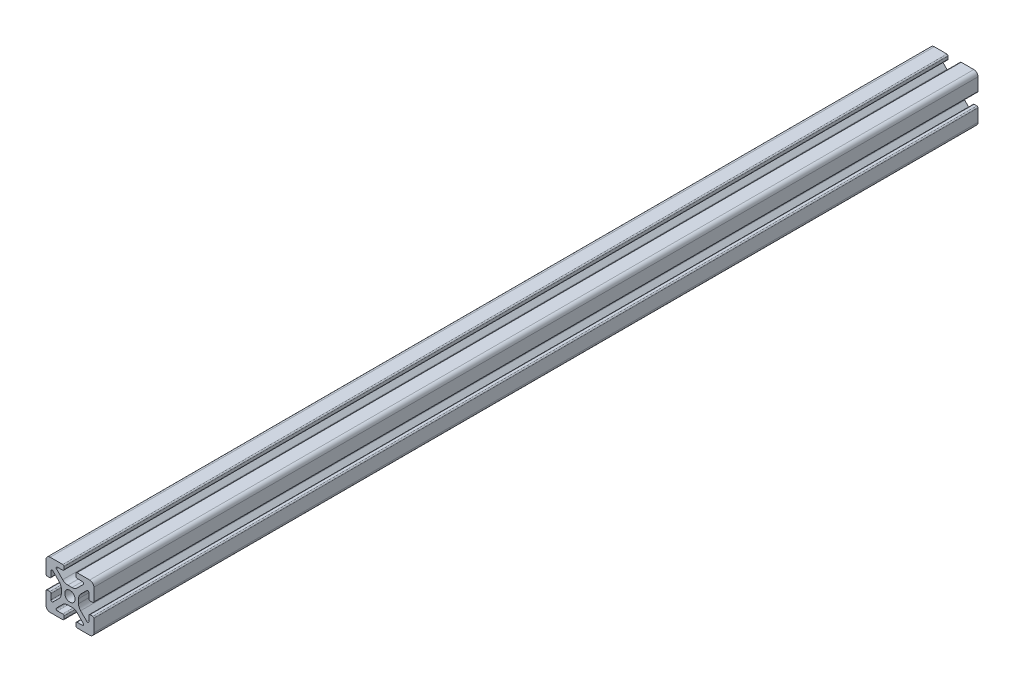
SolidWorks part; units mm, degrees
ref_plane "Front Plane" through (0, 0, 0) normal (0, 0, 1) x (1, 0, 0)
ref_plane "Top Plane" through (0, 0, 0) normal (0, 1, 0) x (1, 0, 0)
ref_plane "Right Plane" through (0, 0, 0) normal (1, 0, 0) x (0, 0, -1)
sketch "Sketch2" plane through (0, 0, 0) normal (0, 0, 1) x (1, 0, 0)
  line L0 (0, 10) -> (0, -10) construction
  line L1 (-10, 0) -> (10, 0) construction
  line L2 (2.5, -10) -> (10, -10)
  line L3 (10, -10) -> (10, -2.5)
  line L4 (2.5, -10) -> (2.5, -7.9246)
  line L5 (2.5, -7.9246) -> (6.4571, -7.9246)
  line L6 (6.4571, -7.9246) -> (2.1325, -3.6)
  line L7 (0, 0) -> (10, -10) construction
  line L8 (10, -2.5) -> (7.9246, -2.5)
  line L9 (7.9246, -2.5) -> (7.9246, -6.4571)
  line L10 (7.9246, -6.4571) -> (3.6, -2.1325)
  line L11 (5.7623, -4.2948) -> (4.2948, -5.7623) construction
  circle A0 centre (0, 0) radius 2.15
  arc A1 (5.25, -7.9246) -> (5.6036, -7.0711) centre (5.25, -7.4246) ccw construction
  point P8 (0, -3.6)
  point P16 (5.0286, -5.0286)
  dimension "Center Hole Diameter" = 4.3
  dimension "D3" = 0.5
  dimension "Rail Height" = 20
  dimension "Rail Width" = 20
  dimension "T-Slot Width" = 5
  dimension "Slot Depth" = 6.4
  dimension "Slot Inner Width" = 11.5
sketch "Sketch3" plane through (0, 0, 0) normal (1, 0, 0) x (0, 0, -1)
  line L0 (-304.8, -10) -> (304.8, -10) construction
  line L1 (-279.4, 0) -> (279.4, 0) construction
  line L2 (0, 10) -> (0, -10) construction
  line L3 (0, 10) -> (0, -10) construction
  point P6 (-279.4, 0)
  point P8 (279.4, 0)
  dimension "Length" = 609.6
  dimension "D1" = 25.4
sketch "Sketch4" plane through (0, 0, 0) normal (0, 0, 1) x (1, 0, 0)
  line L0 (3, -10) -> (8.25, -10)
  line L1 (2.5, -10) -> (10, -10) construction
  line L2 (2.5, -10) -> (2.5, -7.9246) construction
  line L3 (2.5, -7.9246) -> (6.4571, -7.9246) construction
  line L4 (2.5, -8.4246) -> (2.5, -9.5)
  line L5 (3, -7.9246) -> (5.25, -7.9246)
  line L6 (0, -3.6) -> (0.8898, -3.6)
  line L7 (6.4571, -7.9246) -> (2.1325, -3.6) construction
  line L8 (3.0112, -4.4787) -> (5.6036, -7.0711)
  line L9 (10, -10) -> (10, -2.5) construction
  line L10 (7.9246, -6.4571) -> (3.6, -2.1325) construction
  line L11 (7.9246, -2.5) -> (7.9246, -6.4571) construction
  line L12 (7.9246, -5.25) -> (7.9246, -3)
  line L13 (10, -2.5) -> (7.9246, -2.5) construction
  line L14 (8.4246, -2.5) -> (9.5, -2.5)
  line L15 (10, -3) -> (10, -8.25)
  line L16 (7.0711, -5.6036) -> (4.4787, -3.0112)
  line L17 (3.6, 0) -> (3.6, -0.8898)
  line L18 (-10, 0) -> (10, 0) construction
  line L19 (0, -3.6) -> (0, -2.15)
  line L20 (0, 10) -> (0, -10) construction
  line L21 (3.6, 0) -> (2.15, 0)
  arc A0 (2.5, -9.5) -> (3, -10) centre (3, -9.5) ccw
  arc A1 (5.25, -7.9246) -> (5.6036, -7.0711) centre (5.25, -7.4246) ccw construction
  arc A2 (2.5, -8.4246) -> (3, -7.9246) centre (3, -8.4246) cw
  arc A3 (5.25, -7.9246) -> (5.6036, -7.0711) centre (5.25, -7.4246) ccw
  arc A4 (0.8898, -3.6) -> (3.0112, -4.4787) centre (0.8898, -6.6) cw
  arc A5 (8.25, -10) -> (10, -8.25) centre (8.25, -8.25) ccw
  arc A6 (7.0711, -5.6036) -> (7.9246, -5.25) centre (7.4246, -5.25) ccw
  arc A7 (7.9246, -3) -> (8.4246, -2.5) centre (8.4246, -3) cw
  arc A8 (9.5, -2.5) -> (10, -3) centre (9.5, -3) cw
  arc A9 (4.4787, -3.0112) -> (3.6, -0.8898) centre (6.6, -0.8898) cw
  circle A10 centre (0, 0) radius 2.15 construction
  arc A11 (0, -2.15) -> (2.15, 0) centre (0, 0) ccw
  dimension "D1" = 1.75
  dimension "D2" = 3
extrude "Boss-Extrude1" add sketch "Sketch4" along normal mid plane 609.6
mirror "Mirror1" about plane through (0, 0, 0) normal (1, 0, 0) of bodies 134
mirror "Mirror2" about plane through (0, 0, 0) normal (0, 1, 0) of bodies 135
sketch "Sketch5" plane through (0, 0, -304.8) normal (0, 0, -1) x (-1, 0, 0)
  line L1 (-13.8311, 12.3183) -> (13.1641, 12.3183)
  line L2 (-13.8311, 12.3183) -> (-13.8311, -12.3688)
  line L3 (-13.8311, -12.3688) -> (13.1641, -12.3688)
  line L4 (13.1641, 12.3183) -> (13.1641, -12.3688)
extrude "Cut-Extrude1" cut sketch "Sketch5" against normal blind 240.025
equation "\"D3@Sketch2\"=\"T-Slot Width@Sketch2\"*0.1"
equation "\"D1@Sketch4\"=\"D3@Sketch2\"*3.5"
equation "\"D2@Sketch4\"=\"D3@Sketch2\"*6"
equation "\"D1@Boss-Extrude1\"=\"Length@Sketch3\""
